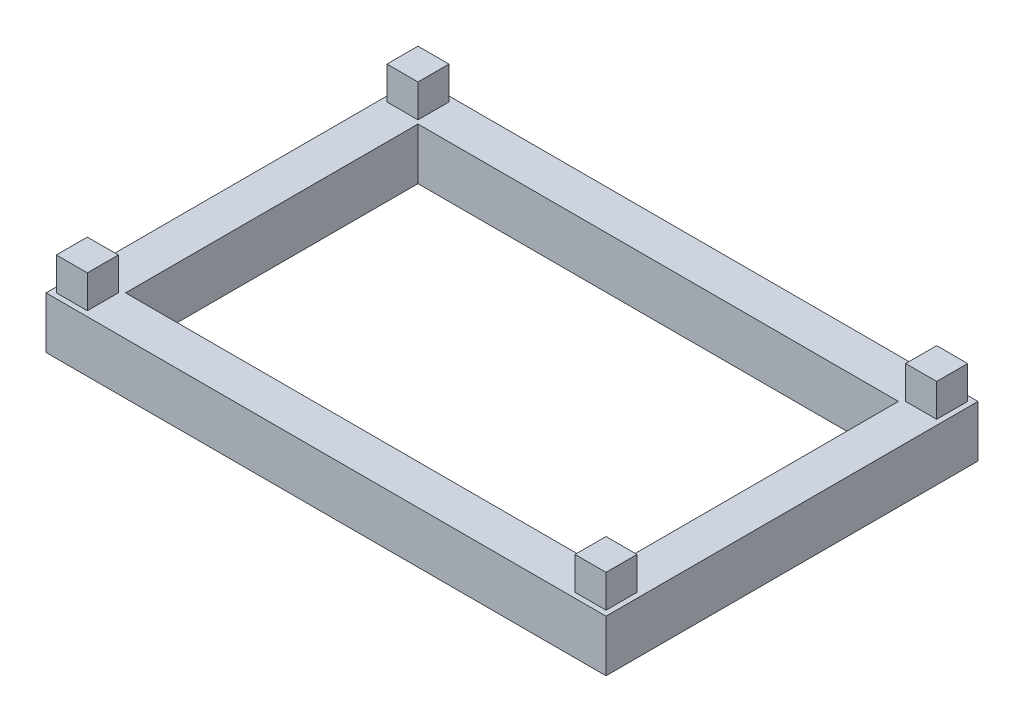
SolidWorks part; units mm, degrees
ref_plane "Front Plane" through (0, 0, 0) normal (0, 0, 1) x (1, 0, 0)
ref_plane "Top Plane" through (0, 0, 0) normal (0, 1, 0) x (1, 0, 0)
ref_plane "Right Plane" through (0, 0, 0) normal (1, 0, 0) x (0, 0, -1)
sketch "Sketch1" plane through (0, 0, 0) normal (0, 1, 0) x (1, 0, 0)
  line L1 (0, 0) -> (108.4, 0)
  line L2 (0, 0) -> (0, 72)
  line L3 (0, 72) -> (108.4, 72)
  line L4 (108.4, 0) -> (108.4, 72)
  dimension "D1" = 72
  dimension "D2" = 108.4
extrude "Boss-Extrude1" add sketch "Sketch1" along normal blind 10
sketch "Sketch2" plane through (0, 10, 0) normal (0, 1, 0) x (1, 0, 0)
  line L25 (7.7, 7.7) -> (100.7, 7.7)
  line L26 (100.7, 7.7) -> (100.7, 64.3)
  line L27 (100.7, 64.3) -> (7.7, 64.3)
  line L28 (7.7, 64.3) -> (7.7, 7.7)
  line L29 (7.7, 7.7) -> (100.7, 7.7)
  line L30 (100.7, 7.7) -> (100.7, 64.3)
  line L31 (100.7, 64.3) -> (7.7, 64.3)
  line L32 (7.7, 64.3) -> (7.7, 7.7)
  dimension "D1" = 7.7
extrude "Cut-Extrude1" cut sketch "Sketch2" against normal through all
sketch "Sketch4" plane through (0, 10, 0) normal (0, 1, 0) x (1, 0, 0)
  line L0 (0, 72) -> (0, 0) construction
  line L1 (1, 7) -> (7, 7)
  line L2 (1, 7) -> (1, 1)
  line L3 (1, 1) -> (7, 1)
  line L4 (7, 7) -> (7, 1)
  line L5 (0, 0) -> (108.4, 0) construction
  dimension "D1" = 6
  dimension "D2" = 6
  dimension "D3" = 1
  dimension "D4" = 1
extrude "Boss-Extrude2" add sketch "Sketch4" along normal blind 6.35
sketch "Sketch5" plane through (0, 10, 0) normal (0, 1, 0) x (1, 0, 0)
  line L0 (0, 0) -> (108.4, 0) construction
  line L1 (101.4, 7) -> (107.4, 7)
  line L2 (101.4, 7) -> (101.4, 1)
  line L3 (101.4, 1) -> (107.4, 1)
  line L4 (107.4, 7) -> (107.4, 1)
  line L5 (108.4, 0) -> (108.4, 72) construction
  dimension "D1" = 6
  dimension "D2" = 6
  dimension "D3" = 1
  dimension "D4" = 1
extrude "Boss-Extrude3" add sketch "Sketch5" along normal blind 6.35
sketch "Sketch6" plane through (0, 10, 0) normal (0, 1, 0) x (1, 0, 0)
  line L6 (108.4, 72) -> (0, 72) construction
  line L7 (1, 71) -> (7, 71)
  line L8 (1, 71) -> (1, 65)
  line L9 (1, 65) -> (7, 65)
  line L10 (7, 71) -> (7, 65)
  line L11 (0, 72) -> (0, 0) construction
  dimension "D1" = 1
  dimension "D2" = 1
  dimension "D3" = 6
  dimension "D4" = 6
extrude "Boss-Extrude4" add sketch "Sketch6" along normal blind 6.35
sketch "Sketch7" plane through (0, 10, 0) normal (0, 1, 0) x (1, 0, 0)
  line L0 (108.4, 72) -> (0, 72) construction
  line L1 (101.4, 71) -> (107.4, 71)
  line L2 (101.4, 71) -> (101.4, 65)
  line L3 (101.4, 65) -> (107.4, 65)
  line L4 (107.4, 71) -> (107.4, 65)
  line L5 (108.4, 0) -> (108.4, 72) construction
  dimension "D1" = 1
  dimension "D2" = 1
  dimension "D3" = 6
  dimension "D4" = 6
extrude "Boss-Extrude5" add sketch "Sketch7" along normal blind 6.35
